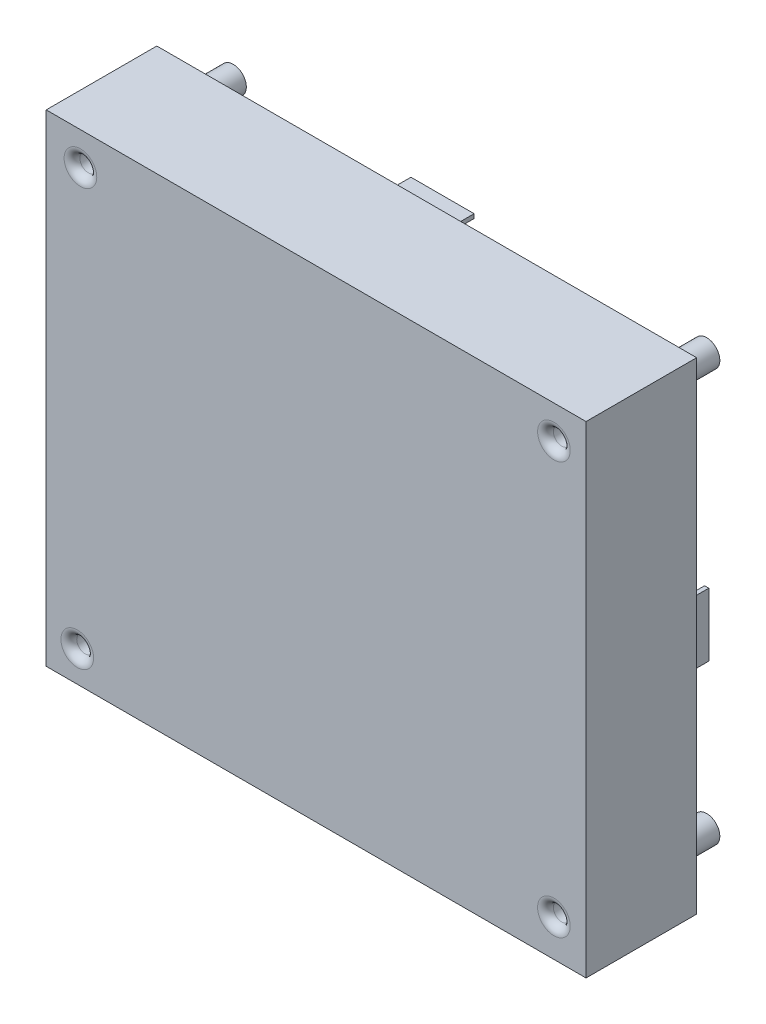
SolidWorks part; units mm, degrees
ref_plane "Спереди" through (0, 0, 0) normal (0, 0, 1) x (1, 0, 0)
ref_plane "Сверху" through (0, 0, 0) normal (0, 1, 0) x (1, 0, 0)
ref_plane "Справа" through (0, 0, 0) normal (1, 0, 0) x (0, 0, -1)
other "Configuration Table"
sketch "Эскиз1" plane through (0, 0, 0) normal (0, 0, 1) x (1, 0, 0)
  line L0 (0, 0) -> (83.9454, 0) construction
  line L1 (-51.25, 45.75) -> (51.25, 45.75)
  line L2 (-51.25, 45.75) -> (-51.25, -45.75)
  line L3 (-51.25, -45.75) -> (51.25, -45.75)
  line L4 (51.25, 45.75) -> (51.25, -45.75)
  line L5 (83.9454, 0) -> (0, 0) construction
  line L6 (0, 0) -> (-81.2162, 0) construction
  line L7 (0, 0) -> (0, 46.6803) construction
  line L8 (0, 46.6803) -> (0, -63.6094) construction
  point P6 (-51.25, 0)
  point P11 (0, 45.75)
  dimension "D1" = 102.5
  dimension "D2" = 91.5
extrude "Бобышка-Вытянуть1" add sketch "Эскиз1" against normal blind 21
sketch "Эскиз2" plane through (0, 0, -21) normal (0, 0, -1) x (-1, 0, 0)
  line L1 (-49.75, 44.5) -> (49.75, 44.5)
  line L2 (-49.75, 44.5) -> (-49.75, -44.5)
  line L3 (-49.75, -44.5) -> (49.75, -44.5)
  line L4 (49.75, 44.5) -> (49.75, -44.5)
  line L6 (0, 0) -> (-59.9598, 0) construction
  line L7 (-59.9598, 0) -> (0, 0) construction
  line L8 (0, 0) -> (0, -50.6293) construction
  point P5 (-49.75, 0)
  point P9 (0, -44.5)
  dimension "D1" = 99.5
  dimension "D2" = 89
extrude "Вырез-Вытянуть1" cut sketch "Эскиз2" against normal blind 19
sketch "Эскиз3" plane through (0, 0, -21) normal (0, 0, -1) x (-1, 0, 0)
  line L0 (51.25, -45.75) -> (-51.25, -45.75) construction
  line L1 (17.25, -45.75) -> (-37.75, -45.75)
  line L2 (17.25, -45.75) -> (17.25, -44.5)
  line L3 (17.25, -44.5) -> (-37.75, -44.5)
  line L4 (-37.75, -45.75) -> (-37.75, -44.5)
  line L5 (-49.75, -44.5) -> (49.75, -44.5) construction
  line L7 (-49.75, 44.5) -> (-49.75, -44.5) construction
  dimension "D1" = 55
  dimension "D2" = 12
extrude "Вырез-Вытянуть2" cut sketch "Эскиз3" against normal blind 3
sketch "Эскиз8" plane through (0, 0, -2) normal (0, 0, -1) x (-1, 0, 0)
  line L0 (49.75, 44.5) -> (-49.75, 44.5) construction
  line L1 (49.75, -44.5) -> (49.75, 44.5) construction
  line L2 (-49.75, -44.5) -> (49.75, -44.5) construction
  line L3 (-49.75, 44.5) -> (-49.75, -44.5) construction
  circle A0 centre (-45.15, 39.5) radius 1.6
  circle A2 centre (44.75, 39.5) radius 1.6
  circle A3 centre (-45.15, -38.75) radius 1.6
  circle A5 centre (45.35, -39.9) radius 1.6
  dimension "D1" = 89.9
  dimension "D2" = 78.25
  dimension "D3" = 90.5073
  dimension "D4" = 79.4
  dimension "D5" = 5
  dimension "D6" = 4.6
  dimension "D7" = 5
  dimension "D8" = 5
  dimension "D9" = 4.4
  dimension "D10" = 4.6
  dimension "D11" = 4.6
  dimension "D12" = 5.75
extrude "Бобышка-Вытянуть2" add sketch "Эскиз8" along normal blind 0.1
sketch "Эскиз9" plane through (0, 0, -2) normal (0, 0, -1) x (-1, 0, 0)
  circle A0 centre (-45.15, 39.5) radius 2.5
  circle A1 centre (44.75, 39.5) radius 2.5
  circle A2 centre (-45.15, -38.75) radius 2.5
  circle A3 centre (45.35, -39.9) radius 2.5
extrude "Бобышка-Вытянуть3" add sketch "Эскиз9" along normal blind 27
sketch "Эскиз10" plane through (0, 0, -21) normal (0, 0, -1) x (-1, 0, 0)
  line L0 (0, 0) -> (-64.103, 0) construction
  line L1 (-64.103, 0) -> (66.2582, 0) construction
  line L2 (66.2582, 0) -> (0, 0) construction
  line L3 (0, 0) -> (0, 51.5546) construction
  line L4 (-49.75, -6) -> (-49.75, 6)
  line L5 (-6, 44.5) -> (6, 44.5)
  line L6 (-6, 44.5) -> (-6, 45.3)
  line L7 (-6, 45.3) -> (6, 45.3)
  line L8 (6, 44.5) -> (6, 45.3)
  line L9 (49.75, 44.5) -> (-49.75, 44.5) construction
  line L10 (-49.75, -6) -> (-50.55, -6)
  line L11 (-50.55, -6) -> (-50.55, 6)
  line L12 (-49.75, 6) -> (-50.55, 6)
  line L14 (-49.75, 44.5) -> (-49.75, -44.5) construction
  line L19 (-49.75, 44.5) -> (-49.75, -44.5) construction
  line L20 (50.55, -6) -> (50.55, 6)
  line L21 (50.55, -6) -> (49.75, -6)
  line L22 (49.75, -6) -> (49.75, 6)
  line L23 (50.55, 6) -> (49.75, 6)
  line L26 (49.75, -44.5) -> (49.75, 44.5) construction
  line L27 (49.75, -44.5) -> (49.75, 44.5) construction
  point P9 (-49.75, 0)
  point P16 (-50.55, 0)
  point P27 (49.75, 0)
  dimension "D1" = 12
  dimension "D2" = 0.8
  dimension "D3" = 0.8
  dimension "D4" = 12
  dimension "D5" = 0.8
  dimension "D6" = 12
sketch "Эскиз12" plane through (0, 0, -29) normal (0, 0, -1) x (-1, 0, 0)
  circle A0 centre (-45.15, 39.5) radius 1.6
  circle A1 centre (44.75, 39.5) radius 1.6
  circle A2 centre (-45.15, -38.75) radius 1.6
  circle A3 centre (45.35, -39.9) radius 1.6
extrude "Вырез-Вытянуть4" cut sketch "Эскиз12" against normal blind 29
fillet "Скругление6" radius 1.5 4 edges at (42.65, 39.5, -2) (-47.25, 39.5, -2) (-47.85, -39.9, -2) (42.65, -38.75, -2)
extrude "Бобышка-Вытянуть4" add sketch "Эскиз10" along normal blind 3
fillet "Скругление7" radius 1.5 4 edges at (-46.95, -39.9, 0) (43.55, -38.75, 0) (43.55, 39.5, 0) (-46.35, 39.5, 0)
